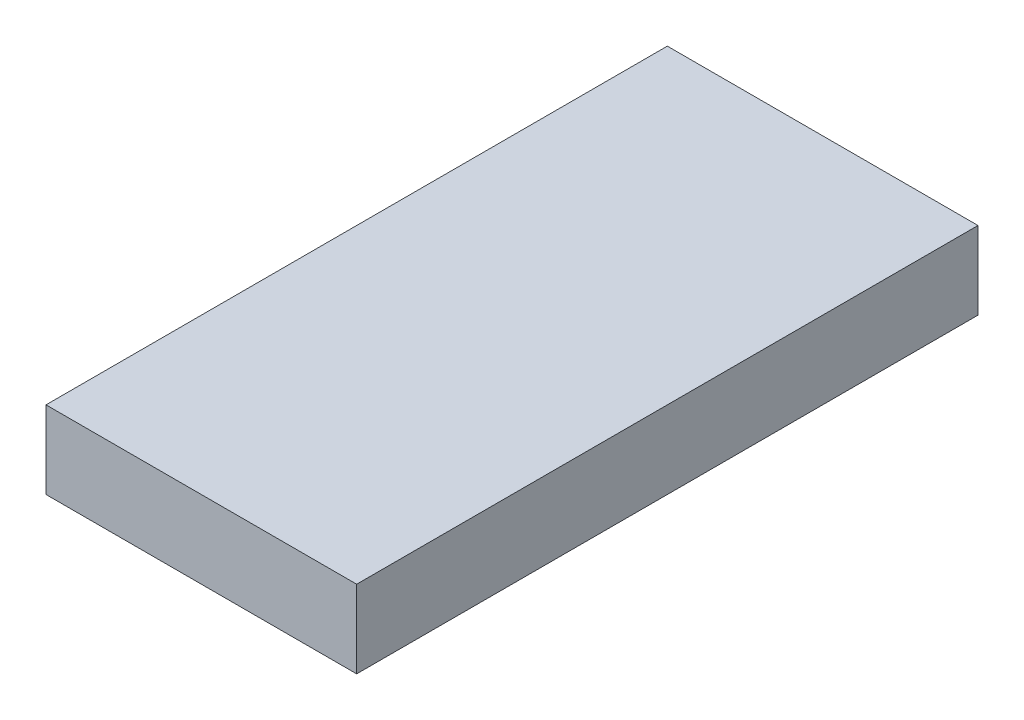
SolidWorks part; units mm, degrees
ref_plane "前视基准面" through (0, 0, 0) normal (0, 0, 1) x (1, 0, 0)
ref_plane "上视基准面" through (0, 0, 0) normal (0, 1, 0) x (1, 0, 0)
ref_plane "右视基准面" through (0, 0, 0) normal (1, 0, 0) x (0, 0, -1)
sketch "草图1" plane through (0, 0, 0) normal (0, 1, 0) x (1, 0, 0)
  line L1 (-10, -20) -> (10, -20)
  line L2 (-10, -20) -> (-10, 20)
  line L3 (-10, 20) -> (10, 20)
  line L4 (10, -20) -> (10, 20)
  line L5 (-10, -20) -> (10, 20) construction
  line L6 (-10, 20) -> (10, -20) construction
  point P0 (0, 0)
  dimension "D1" = 20
  dimension "D2" = 40
extrude "凸台-拉伸1" add sketch "草图1" along normal blind 5
sketch "草图2" plane through (0, 5, 0) normal (0, 1, 0) x (1, 0, 0)
  circle A0 centre (-6.0466, 14.0074) radius 1.5
  circle A1 centre (5.6212, 13.582) radius 1.5
  circle A2 centre (-7.2139, -16.0128) radius 1.5
  circle A3 centre (6.6105, -16.0128) radius 1.5
  dimension "D1" = 3
  dimension "D2" = 3
  dimension "D3" = 3
  dimension "D4" = 3
